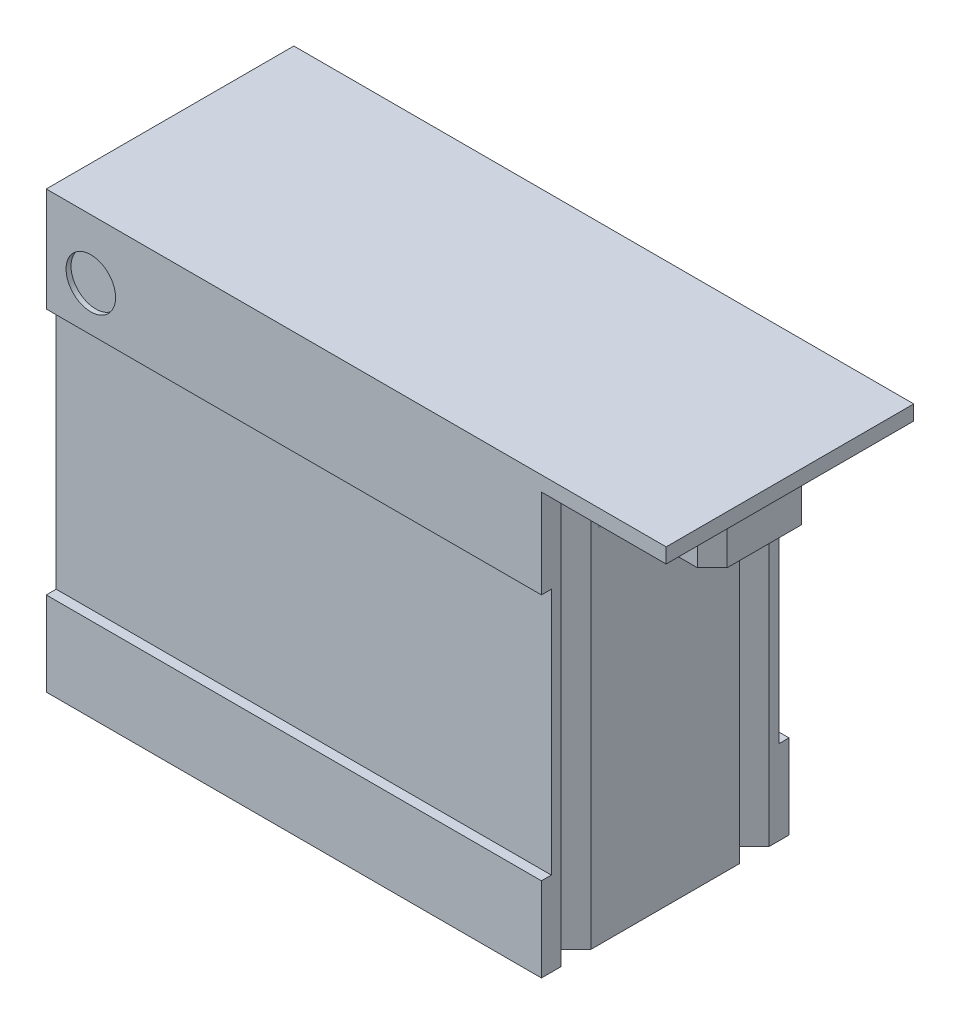
SolidWorks part; units mm, degrees
material "Zinc AC41A Alloy, As Cast"
ref_plane "Front Plane" through (0, 0, 0) normal (0, 0, 1) x (1, 0, 0)
ref_plane "Top Plane" through (0, 0, 0) normal (0, 1, 0) x (1, 0, 0)
ref_plane "Right Plane" through (0, 0, 0) normal (1, 0, 0) x (0, 0, -1)
sketch "Sketch11" plane through (0, 0, 0) normal (0, 1, 0) x (1, 0, 0)
  line L1 (0, 0) -> (10, 0)
  line L2 (0, 0) -> (0, 5)
  line L3 (0, 5) -> (10, 5)
  line L4 (10, 0) -> (10, 5)
  dimension "D1" = 5
  dimension "D2" = 10
extrude "Boss-Extrude2" add sketch "Sketch11" along normal blind 8.5
sketch "Sketch12" plane through (10, 0, 0) normal (1, 0, 0) x (0, 0, -1)
  line L0 (0, 8.5) -> (0, 6.7)
  line L1 (0, 8.5) -> (0, 0) construction
  line L2 (0, 6.7) -> (0.2, 6.7)
  line L3 (0.2, 6.7) -> (0.2, 1.7)
  line L4 (0, 8.5) -> (5, 8.5) construction
  line L5 (4.8, 1.7) -> (5, 1.7)
  line L6 (2.5, 8.5) -> (2.5, 0) construction
  line L7 (0, 0) -> (5, 0) construction
  line L8 (5, 8.5) -> (0, 8.5)
  line L9 (5, 0) -> (0, 0)
  line L10 (0, 0) -> (0, 1.7)
  line L11 (5, 0) -> (5, 1.7)
  line L12 (0.2, 1.7) -> (0, 1.7)
  line L13 (4.8, 6.7) -> (4.8, 1.7)
  line L14 (5, 6.7) -> (4.8, 6.7)
  line L15 (5, 8.5) -> (5, 6.7)
  dimension "D1" = 1.8
  dimension "D2" = 0.2
  dimension "D3" = 5
  dimension "D4" = 90
  dimension "D5" = 1.7
extrude "Cut-Extrude1" cut sketch "Sketch12" against normal blind 11 flip side to cut
sketch "Sketch13" plane through (0, 8.5, 0) normal (0, -1, 0) x (1, 0, 0)
  line L0 (0, -2.5) -> (10, -2.5) construction
  line L1 (0, -5) -> (0, 0) construction
  line L2 (10, 0) -> (10, -5) construction
  line L3 (5, 0) -> (5, -5) construction
  line L4 (0, 0) -> (10, 0) construction
  line L5 (10, -5) -> (0, -5) construction
  line L6 (1, -0.6) -> (9, -0.6)
  line L7 (9.2, -0.8) -> (9.2, -4.2)
  line L8 (0.8, -0.8) -> (0.8, -4.2)
  line L11 (0.6467, -1.5741) -> (0.6467, -3.5741) construction
  line L12 (9.393, -1.5) -> (0.607, -1.5) construction
  line L13 (9.393, -1.5) -> (9.393, -3.5) construction
  line L14 (9.393, -3.5) -> (0.607, -3.5) construction
  line L15 (0.607, -1.5) -> (0.607, -3.5) construction
  line L16 (0.6467, -1.5741) -> (9.3467, -1.5741) construction
  line L17 (0.6467, -3.5741) -> (9.3467, -3.5741) construction
  line L18 (9.3467, -1.5741) -> (9.3467, -3.5741) construction
  line L19 (1, -4.4) -> (9, -4.4)
  arc A0 (0.8, -4.2) -> (1, -4.4) centre (1, -4.2) ccw
  arc A1 (0.8, -0.8) -> (1, -0.6) centre (1, -0.8) cw
  arc A2 (9, -4.4) -> (9.2, -4.2) centre (9, -4.2) ccw
  arc A3 (9.2, -0.8) -> (9, -0.6) centre (9, -0.8) ccw
  point P24 (0.5, -2.5)
  point P34 (9.5, -2.5)
  dimension "D3" = 4.2
  dimension "D4" = 0.2
  dimension "D5" = 1.9
  dimension "D6" = 0.2
  dimension "D1" = 1.9
  dimension "D2" = 4.2
  dimension "D8" = 2
  dimension "D9" = 8.7861
  dimension "D10" = 8.7
  dimension "D11" = 2
  dimension "D13" = 0.9259
extrude "Cut-Extrude2" cut sketch "Sketch13" along normal blind 8.3
sketch "Sketch18" plane through (0, 8.5, 0) normal (0, 1, 0) x (1, 0, 0)
  line L0 (5, 5) -> (5, 0) construction
  line L1 (1.5, 3.8556) -> (4.2, 3.8556)
  line L2 (1.5, 3.8556) -> (1.5, 4.4)
  line L3 (1.7, 4.6) -> (4, 4.6)
  line L4 (4.2, 3.8556) -> (4.2, 4.4)
  line L5 (10, 5) -> (0, 5) construction
  line L6 (0, 0) -> (10, 0) construction
  line L7 (0, 2.5) -> (10, 2.5) construction
  line L8 (0, 5) -> (0, 0) construction
  line L9 (10, 0) -> (10, 5) construction
  arc A0 (4, 4.6) -> (4.2, 4.4) centre (4, 4.4) cw
  arc A1 (1.5, 4.4) -> (1.7, 4.6) centre (1.7, 4.4) cw
  point P18 (4.2, 4.6)
  point P21 (1.5, 4.6)
  dimension "D4" = 0.2
  dimension "D1" = 0.8
  dimension "D2" = 2.7
  dimension "D3" = 2.1
extrude "Cut-Extrude6" cut sketch "Sketch18" against normal blind 6
sketch "Sketch14" plane through (0, 8.5, 0) normal (0, -1, 0) x (1, 0, 0)
  line L0 (5, -5) -> (5, 0) construction
  line L1 (10, -5) -> (0, -5) construction
  line L2 (0, 0) -> (10, 0) construction
  line L3 (8.5, -4.6) -> (1.5, -4.6)
  line L4 (10, -2.5) -> (0, -2.5) construction
  line L5 (10, 0) -> (10, -5) construction
  line L6 (0, -5) -> (0, 0) construction
  line L7 (8.5, -0.4) -> (1.5, -0.4)
  line L16 (9.5, -3.6) -> (9.5, -1.4)
  line L19 (0.5, -1.4) -> (0.5, -3.6)
  arc A0 (9.5, -3.6) -> (8.5, -4.6) centre (8.5, -3.6) cw
  arc A1 (1.5, -0.4) -> (0.5, -1.4) centre (1.5, -1.4) ccw
  arc A2 (9.5, -1.4) -> (8.5, -0.4) centre (8.5, -1.4) ccw
  arc A3 (1.5, -4.6) -> (0.5, -3.6) centre (1.5, -3.6) cw
  point P0 (9.5, -2.5)
  point P24 (0.5, -2.5)
  dimension "D2" = 1
  dimension "D7" = 1
  dimension "D3" = 4.5
  dimension "D4" = 4.5
  dimension "D8" = 2.1
extrude "Cut-Extrude3" cut sketch "Sketch14" along normal blind 1.5
sketch "Sketch15" plane through (0, 8.5, 0) normal (0, 1, 0) x (1, 0, 0)
  line L0 (0.5, 1.4) -> (0.5, 3.6) construction
  line L1 (0.6, 3.6) -> (9.4, 3.6)
  line L2 (0.5, 3.5) -> (0.5, 1.5)
  line L3 (0.6, 1.4) -> (9.4, 1.4)
  line L4 (9.5, 3.5) -> (9.5, 1.5)
  line L5 (9.5, 3.6) -> (9.5, 1.4) construction
  line L6 (0, 2.5) -> (10, 2.5) construction
  line L7 (0, 5) -> (0, 0) construction
  line L8 (10, 0) -> (10, 5) construction
  arc A0 (9.4, 1.4) -> (9.5, 1.5) centre (9.4, 1.5) ccw
  arc A1 (9.4, 3.6) -> (9.5, 3.5) centre (9.4, 3.5) cw
  arc A2 (0.5, 1.5) -> (0.6, 1.4) centre (0.6, 1.5) ccw
  arc A3 (0.6, 3.6) -> (0.5, 3.5) centre (0.6, 3.5) ccw
  point P16 (9.5, 1.4)
  point P23 (0.5, 3.6)
  dimension "D3" = 0.1
  dimension "D1" = 1.1
  dimension "D2" = 1.1
extrude "Cut-Extrude4" cut sketch "Sketch15" against normal blind 8.3
sketch "Sketch16" plane through (0, 0, 0) normal (-1, 0, 0) x (0, 0, 1)
  line L0 (-4.8395, 0.9395) -> (-4.1, 0.2)
  line L1 (-3.6, 0.2) -> (-4.2, 0.2) construction
  line L2 (-0.9, 0.2) -> (-0.0406, 1.0594)
  line L3 (-0.8, 0.2) -> (-1.4, 0.2) construction
  line L4 (-5, 0) -> (0, 0) construction
  line L5 (-4.1, 0.2) -> (-4.8395, 0.2)
  line L6 (-4.8395, 0.2) -> (-4.8395, 0.9395)
  line L9 (-0.0406, 1.0594) -> (-0.0406, 0.2)
  line L10 (-0.0406, 0.2) -> (-0.9, 0.2)
  line L11 (-5, 1.7) -> (-5, 0) construction
  line L12 (0, 1.7) -> (0, 0) construction
  dimension "D1" = 45
  dimension "D2" = 45
  dimension "D3" = 0.9
  dimension "D4" = 0.9
extrude "Boss-Extrude3" add sketch "Sketch16" against normal blind 9.5
sketch "Sketch17" plane through (0, 8.5, 0) normal (0, 1, 0) x (1, 0, 0)
  line L0 (0, 2.5) -> (10, 2.5) construction
  line L1 (0, 5) -> (0, 0) construction
  line L2 (10, 0) -> (10, 5) construction
  line L3 (5, 5) -> (5, 0) construction
  line L4 (10, 5) -> (0, 5) construction
  line L5 (0, 0) -> (10, 0) construction
  line L6 (-0.2423, 4.8423) -> (0.3, 4.3)
  line L7 (0.3, 4.3) -> (-0.2423, 3.7577)
  line L8 (-0.2423, 3.7577) -> (-0.2423, 4.8423)
  line L9 (10.2423, 3.7577) -> (10.2423, 4.8423)
  line L10 (9.7, 4.3) -> (10.2423, 3.7577)
  line L11 (10.2423, 4.8423) -> (9.7, 4.3)
  line L12 (10.2423, 0.1577) -> (9.7, 0.7)
  line L13 (9.7, 0.7) -> (10.2423, 1.2423)
  line L14 (10.2423, 1.2423) -> (10.2423, 0.1577)
  line L15 (-0.2423, 1.2423) -> (-0.2423, 0.1577)
  line L16 (0.3, 0.7) -> (-0.2423, 1.2423)
  line L17 (-0.2423, 0.1577) -> (0.3, 0.7)
  dimension "D1" = 90
  dimension "D2" = 135
  dimension "D3" = 0.3
  dimension "D4" = 1.8
extrude "Cut-Extrude5" cut sketch "Sketch17" against normal blind 9.5
sketch "Sketch19" plane through (0, 0, 0) normal (0, 0, 1) x (1, 0, 0)
  line L0 (0, 8.5) -> (10, 8.5) construction
  line L1 (0, 8.5) -> (0, 6.7) construction
  circle A0 centre (0.9, 7.6) radius 0.5
  dimension "D2" = 0.9
  dimension "D3" = 1
  dimension "D1" = 0.9
extrude "Cut-Extrude7" cut sketch "Sketch19" against normal blind 0.1
sketch "Sketch20" plane through (0, 0, -5) normal (0, 0, -1) x (-1, 0, 0)
  line L0 (-10, 8.5) -> (0, 8.5) construction
  line L1 (0, 8.5) -> (0, 6.7) construction
  circle A0 centre (-0.9, 7.6) radius 0.5
  dimension "D2" = 0.9
  dimension "D3" = 1
  dimension "D1" = 0.9
extrude "Cut-Extrude8" cut sketch "Sketch20" against normal blind 0.1
sketch "Sketch21" plane through (0, 8.5, 0) normal (0, 1, 0) x (1, 0, 0)
  line L0 (10, 1) -> (10, 4) construction
  line L1 (10.3, 3.55) -> (11.7, 3.55)
  line L2 (10, 1.15) -> (10, 1)
  line L3 (10.3, 1.45) -> (11.7, 1.45)
  line L4 (12, 3.25) -> (12, 1.75)
  line L5 (9.5554, 3.9764) -> (10, 3.9764)
  line L6 (9.5554, 3.9764) -> (9.5554, 1)
  line L7 (9.5554, 1) -> (10, 1)
  line L8 (10, 3.9764) -> (10, 3.85)
  line L9 (10, 2.5) -> (0, 2.5) construction
  line L10 (11.7, 3.55) -> (12, 3.25)
  line L11 (11.7, 1.45) -> (12, 1.75)
  circle A0 centre (11, 2.5) radius 0.425
  arc A1 (10.3, 1.45) -> (10, 1.15) centre (10.3, 1.15) ccw
  arc A2 (10.3, 3.55) -> (10, 3.85) centre (10.3, 3.85) cw
  point P1 (12, 1.45)
  point P3 (12, 3.55)
  point P20 (10, 1.45)
  dimension "D4" = 0.85
  dimension "D7" = 0.3
  dimension "D1" = 1.05
  dimension "D2" = 1.05
  dimension "D3" = 2
  dimension "D5" = 1
  dimension "D6" = 1.05
extrude "Boss-Extrude4" add sketch "Sketch21" against normal blind 1.2
sketch "Sketch22" plane through (0, 0.2, 0) normal (0, 1, 0) x (1, 0, 0)
  line L1 (0.3863, 4.706) -> (9.6052, 4.706)
  line L2 (0.3863, 4.706) -> (0.3863, 0.2601)
  line L3 (0.3863, 0.2601) -> (9.6052, 0.2601)
  line L4 (9.6052, 4.706) -> (9.6052, 0.2601)
extrude "Boss-Extrude5" add sketch "Sketch22" along normal blind 8.2
sketch "Sketch23" plane through (0, 8.5, 0) normal (0, 1, 0) x (1, 0, 0)
  line L0 (0, 2.5) -> (12, 2.5) construction
  line L1 (0, 4) -> (0, 1) construction
  line L2 (12, 1.75) -> (12, 3.25) construction
  line L3 (5, 0.4) -> (5, 5) construction
  line L4 (8.5, 0.4) -> (1.5, 0.4) construction
  line L5 (10, 5) -> (0, 5) construction
  line L7 (12.5189, 5) -> (0, 5)
  line L8 (12.5189, 5) -> (12.5189, 0)
  line L9 (12.5189, 0) -> (0, 0)
  line L10 (0, 5) -> (0, 0)
  line L11 (12.5189, 5) -> (0, 0) construction
  line L12 (12.5189, 0) -> (0, 5) construction
  point P12 (6.2595, 2.5)
  dimension "D1" = 12.5189
extrude "Boss-Extrude6" add sketch "Sketch23" along normal blind 0.3
